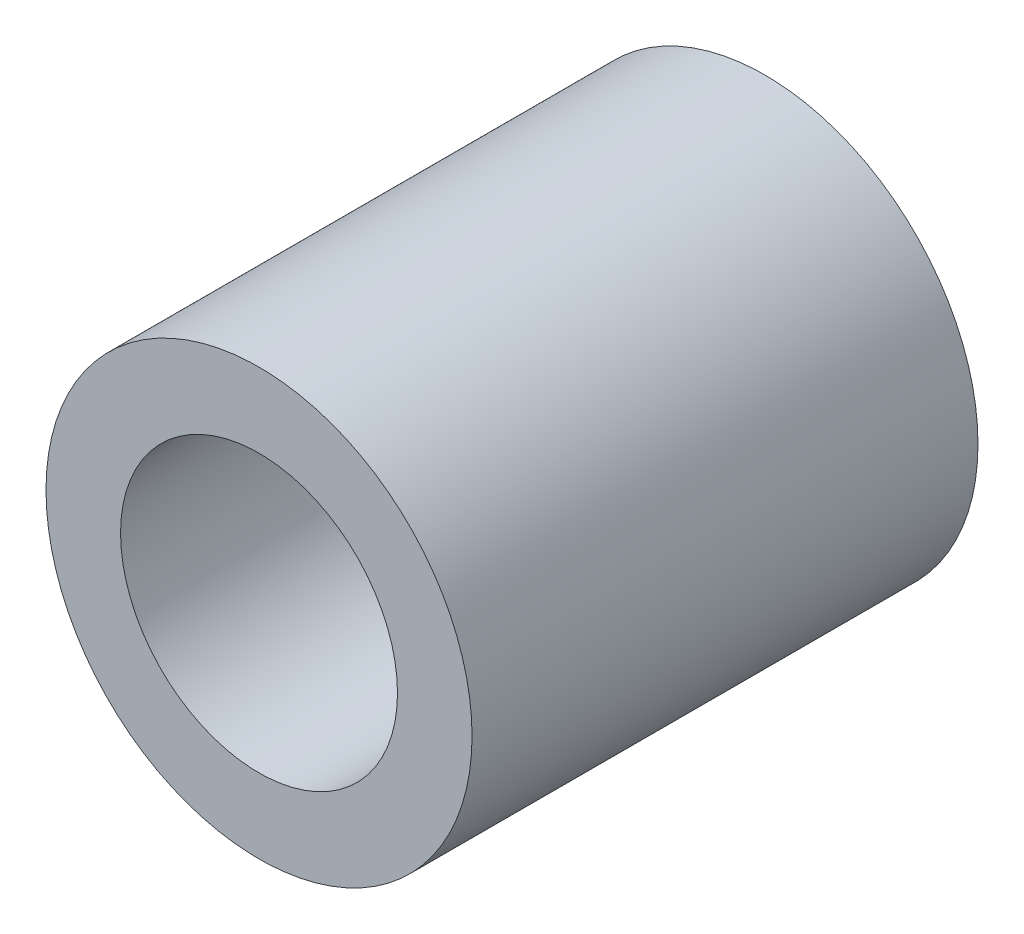
SolidWorks part; units mm, degrees
ref_plane "Alzado" through (0, 0, 0) normal (0, 0, 1) x (1, 0, 0)
ref_plane "Planta" through (0, 0, 0) normal (0, 1, 0) x (1, 0, 0)
ref_plane "Vista lateral" through (0, 0, 0) normal (1, 0, 0) x (0, 0, -1)
sketch "Croquis1" plane through (0, 0, 0) normal (0, 0, 1) x (1, 0, 0)
  circle A0 centre (0, 0) radius 4
  circle A1 centre (0, 0) radius 2.6
  dimension "D1" = 8
  dimension "D2" = 5.2
extrude "Saliente-Extruir1" add sketch "Croquis1" along normal blind 9.5
